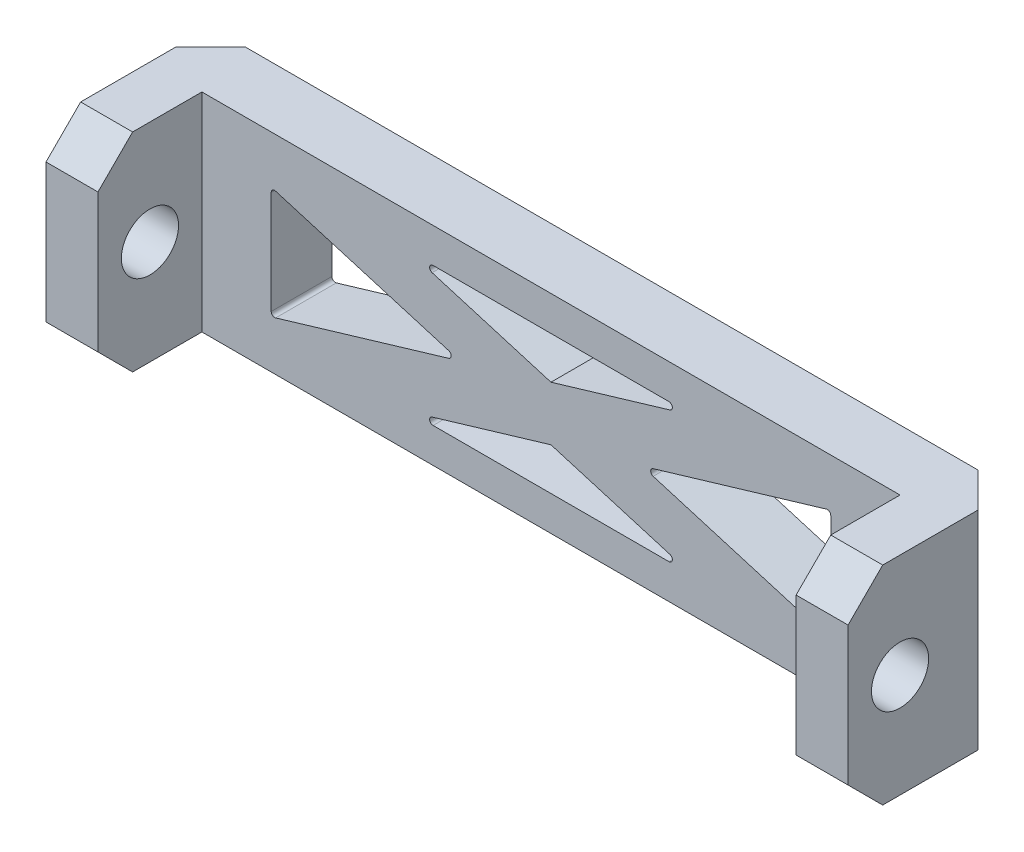
SolidWorks part; units mm, degrees
ref_plane "前视基准面" through (0, 0, 0) normal (0, 0, 1) x (1, 0, 0)
ref_plane "上视基准面" through (0, 0, 0) normal (0, 1, 0) x (1, 0, 0)
ref_plane "右视基准面" through (0, 0, 0) normal (1, 0, 0) x (0, 0, -1)
other "Configuration Table"
sketch "草图1" plane through (0, 0, 0) normal (0, 0, 1) x (1, 0, 0)
  line L1 (-23.15, 6) -> (23.15, 6)
  line L2 (-23.15, 6) -> (-23.15, -6)
  line L3 (-23.15, -6) -> (23.15, -6)
  line L4 (23.15, 6) -> (23.15, -6)
  line L5 (-23.15, 6) -> (23.15, -6) construction
  line L6 (-23.15, -6) -> (23.15, 6) construction
  point P0 (0, 0)
  dimension "D1" = 46.3
  dimension "D2" = 12
extrude "凸台-拉伸1" add sketch "草图1" along normal blind 3.5
sketch "草图2" plane through (0, 0, 3.5) normal (0, 0, 1) x (1, 0, 0)
  line L0 (0, 6) -> (0, -6) construction
  line L1 (-23.15, 6) -> (-20.15, 6)
  line L2 (-23.15, 6) -> (-23.15, -6)
  line L3 (-23.15, -6) -> (-20.15, -6)
  line L4 (-20.15, 6) -> (-20.15, -6)
  line L5 (23.15, 6) -> (-23.15, 6) construction
  line L6 (-23.15, -6) -> (23.15, -6) construction
  line L7 (23.15, -6) -> (20.15, -6)
  line L8 (20.15, 6) -> (20.15, -6)
  line L9 (23.15, 6) -> (20.15, 6)
  line L10 (23.15, 6) -> (23.15, -6)
  dimension "D1" = 3
extrude "凸台-拉伸2" add sketch "草图2" along normal blind 6
sketch "草图3" plane through (-20.15, 0, 0) normal (1, 0, 0) x (0, 0, -1)
  line L0 (-10.149, 0.0035) -> (-3.5, 0) construction
  line L4 (-3.5, -6) -> (-3.5, 6)
  line L5 (-3.5, 6) -> (-9.5, 6)
  line L6 (-9.5, 6) -> (-9.5, -6)
  line L7 (-9.5, -6) -> (-3.5, -6)
  line L8 (-3.5, -6) -> (-3.5, 6) construction
  line L9 (-3.5, 6) -> (-9.5, 6) construction
  line L10 (-9.5, 6) -> (-9.5, -6) construction
  line L11 (-9.5, -6) -> (-3.5, -6) construction
  circle A0 centre (-6.5, 0.0016) radius 1.65
  dimension "D3" = 3.3
  dimension "D2" = 3
  dimension "D1" = 0
extrude "切除-拉伸1" cut sketch "草图3" against normal through all both and the other way through all
chamfer "倒角1" distance 2 angle 45 2 edges at (-23.15, 0, 0) (23.15, 0, 0)
chamfer "倒角2" distance 2 angle 45 4 edges at (-21.65, -6, 9.5) (21.65, -6, 9.5) (-21.65, 6, 9.5) (21.65, 6, 9.5)
sketch "草图4" plane through (0, 0, 3.5) normal (0, 0, 1) x (1, 0, 0)
  line L0 (-20.15, 6) -> (20.15, -6) construction
  line L1 (20.15, 6) -> (-20.15, -6) construction
  line L2 (-20.15, -6) -> (-20.15, 6) construction
  line L3 (-8.1773, 4) -> (8.1773, 4)
  line L4 (8.1773, 4) -> (0, 1.5651)
  line L5 (0, 1.5651) -> (-8.1773, 4)
  line L6 (-16.15, 3.2438) -> (-16.15, -3.2438)
  line L7 (-16.15, -3.2438) -> (-5.2561, 0)
  line L8 (-5.2561, 0) -> (-16.15, 3.2438)
  line L9 (0, 6) -> (0, -6) construction
  line L10 (20.15, 6) -> (-20.15, 6) construction
  line L11 (-20.15, -6) -> (20.15, -6) construction
  line L12 (-20.15, 0) -> (20.15, 0) construction
  line L13 (20.15, 6) -> (20.15, -6) construction
  line L14 (8.1773, -4) -> (0, -1.5651)
  line L15 (-8.1773, -4) -> (8.1773, -4)
  line L16 (0, -1.5651) -> (-8.1773, -4)
  line L17 (16.15, -3.2438) -> (5.2561, 0)
  line L18 (16.15, 3.2438) -> (16.15, -3.2438)
  line L19 (5.2561, 0) -> (16.15, 3.2438)
  dimension "D1" = 1.5
  dimension "D2" = 2
  dimension "D3" = 1.5
  dimension "D4" = 4
extrude "切除-拉伸2" cut sketch "草图4" against normal through all both and the other way through all
fillet "圆角1" radius 0.2 10 edges at (-5.2561, 0, 1.75) (5.2561, 0, 1.75) (8.1773, -4, 1.75) (16.15, -3.2438, 1.75) (-16.15, -3.2438, 1.75) (-8.1773, 4, 1.75) (8.1773, 4, 1.75) (16.15, 3.2438, 1.75) (-16.15, 3.2438, 1.75) (-8.1773, -4, 1.75)
